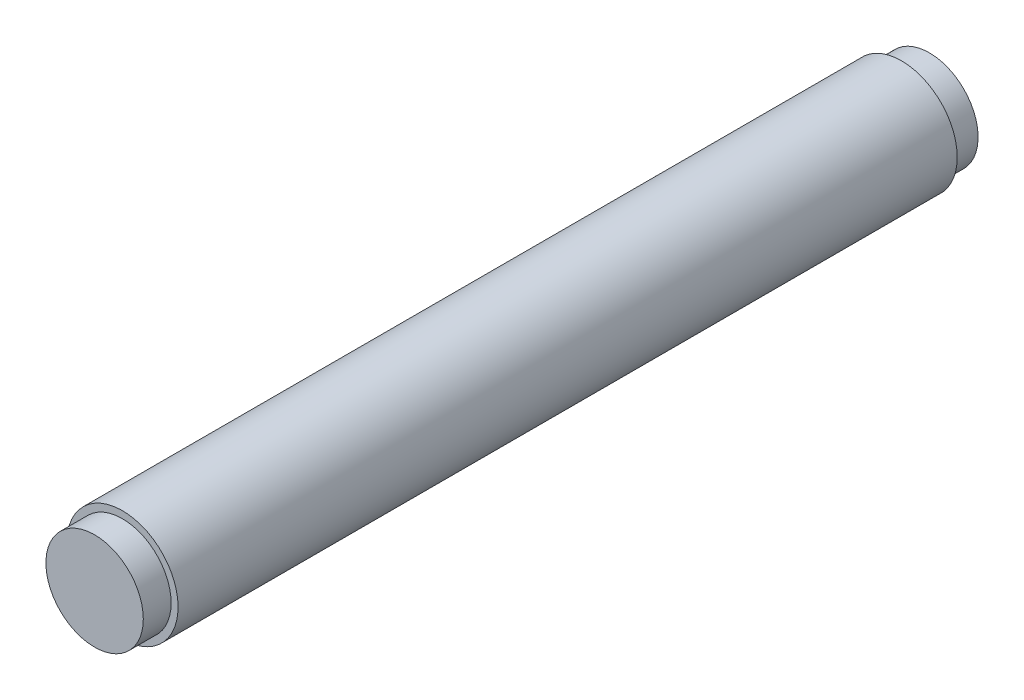
SolidWorks part; units mm, degrees
ref_plane "Front Plane" through (0, 0, 0) normal (0, 0, 1) x (1, 0, 0)
ref_plane "Top Plane" through (0, 0, 0) normal (0, 1, 0) x (1, 0, 0)
ref_plane "Right Plane" through (0, 0, 0) normal (1, 0, 0) x (0, 0, -1)
sketch "Sketch1" plane through (0, 0, 0) normal (0, 0, 1) x (1, 0, 0)
  circle A0 centre (0, 0) radius 25.4
  dimension "D1" = 50.8
extrude "Boss-Extrude1" add sketch "Sketch1" against normal blind 381 from offset 190.5
sketch "Sketch2" plane through (0, 0, 190.5) normal (0, 0, 1) x (1, 0, 0)
  circle A0 centre (0, 0) radius 22.225
  circle A1 centre (0, 0) radius 25.4
extrude "Cut-Extrude1" cut sketch "Sketch2" against normal blind 12.7
sketch "Sketch3" plane through (0, 0, -190.5) normal (0, 0, -1) x (-1, 0, 0)
  circle A0 centre (0, 0) radius 22.225
  circle A1 centre (0, 0) radius 25.4
extrude "Cut-Extrude2" cut sketch "Sketch3" against normal blind 12.7
